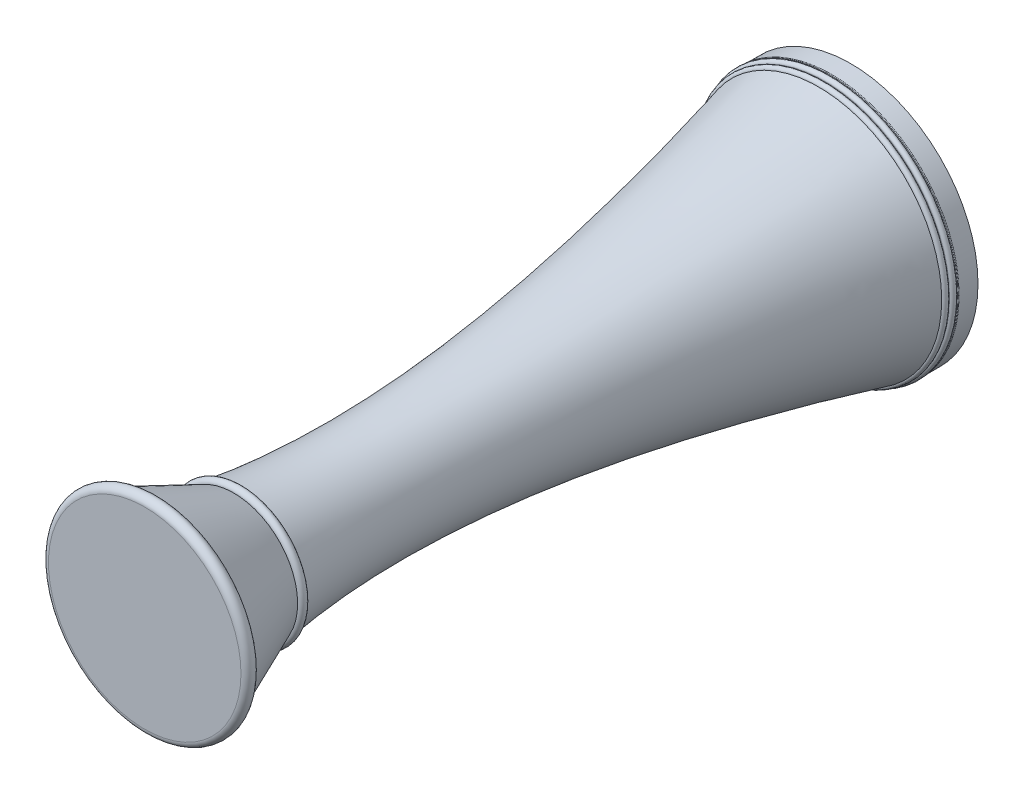
SolidWorks part; units mm, degrees
ref_plane "Front Plane" through (0, 0, 0) normal (0, 0, 1) x (1, 0, 0)
ref_plane "Top Plane" through (0, 0, 0) normal (0, 1, 0) x (1, 0, 0)
ref_plane "Right Plane" through (0, 0, 0) normal (1, 0, 0) x (0, 0, -1)
sketch "Sketch1" plane through (0, 0, 0) normal (0, 0, 1) x (1, 0, 0)
  circle A0 centre (0, 0) radius 5
  dimension "D1" = 10
extrude "Boss-Extrude1" add sketch "Sketch1" along normal blind 0.75
sketch "Sketch5" plane through (0, 0, 0) normal (0, 1, 0) x (1, 0, 0)
  line L0 (0, 0) -> (0, -50.8181) construction
sketch "Sketch7" plane through (0, 0, 0) normal (0, 1, 0) x (1, 0, 0)
  line L0 (-5, -0.75) -> (5, -0.75) construction
  line L2 (0, -0.75) -> (5, -0.75)
  line L3 (5, -0.7887) -> (0, -0.7887)
  line L4 (0, 0) -> (0, -50.8181) construction
  line L5 (0, -0.7887) -> (0, -0.75)
  arc A0 (5, -0.75) -> (5, -0.7887) centre (5, -0.7693) cw
revolve "Revolve1" add sketch "Sketch7" angle 360 about L5
sketch "Sketch8" plane through (0, 0, 0) normal (0, 1, 0) x (1, 0, 0)
  line L0 (0, -0.7887) -> (4.9111, -0.7887)
  line L1 (-5, -0.7887) -> (5, -0.7887) construction
  line L2 (4.9111, -1.0247) -> (0, -1.0247)
  line L3 (0, 0) -> (0, -50.8181) construction
  line L4 (0, -1.0247) -> (0, -0.7887)
  arc A0 (4.9111, -0.7887) -> (4.9111, -1.0247) centre (4.9111, -0.9067) cw
revolve "Revolve2" add sketch "Sketch8" angle 360 about L4
sketch "Sketch10" plane through (0, 0, 0) normal (0, 1, 0) x (1, 0, 0)
  line L0 (0, -1.0247) -> (4.8359, -1.0247)
  line L1 (-4.9111, -1.0247) -> (4.9111, -1.0247) construction
  line L2 (4.8359, -1.2631) -> (0, -1.2631)
  line L3 (0, 0) -> (0, -50.8181) construction
  line L4 (0, -1.2631) -> (0, -1.0247)
  arc A0 (4.8359, -1.0247) -> (4.8359, -1.2631) centre (4.8359, -1.1439) cw
revolve "Revolve3" add sketch "Sketch10" angle 360 about L4
sketch "Sketch11" plane through (0, 0, 0) normal (0, 1, 0) x (1, 0, 0)
  line L2 (4.8359, -1.2631) -> (1.2181, -15.5203) construction
  line L3 (1.2181, -15.5203) -> (2.5102, -23.9242) construction
  line L4 (2.5102, -23.9242) -> (0, -23.9242)
  line L5 (0, 0) -> (0, -50.8181) construction
  line L6 (0, -23.9242) -> (0, -1.2631)
  line L7 (-4.8359, -1.2631) -> (4.8359, -1.2631) construction
  line L8 (0, -1.2631) -> (4.8359, -1.2631)
  spline S0 degree 2 poles (4.8359, -1.2631) (1.2181, -15.5203) (2.5102, -23.9242) knots 0 0 0 1 1 1
revolve "Revolve4" add sketch "Sketch11" angle 360 about L6
sketch "Sketch12" plane through (0, 0, 0) normal (0, 1, 0) x (1, 0, 0)
  line L0 (0, -23.9242) -> (2.5102, -23.9242)
  line L1 (-2.5102, -23.9242) -> (2.5102, -23.9242) construction
  line L2 (2.5102, -24.2568) -> (0, -24.2568)
  line L3 (0, 0) -> (0, -50.8181) construction
  line L4 (0, -24.2568) -> (0, -23.9242)
  arc A0 (2.5102, -23.9242) -> (2.5102, -24.2568) centre (2.5102, -24.0905) cw
revolve "Revolve5" add sketch "Sketch12" angle 360 about L4
sketch "Sketch14" plane through (0, 0, 24.2568) normal (0, 0, 1) x (1, 0, 0)
  circle A0 centre (0, 0) radius 2.5102
extrude "Boss-Extrude2" add sketch "Sketch14" along normal blind 3 draft 23 draft outward yes
sketch "Sketch15" plane through (0, 0, 0) normal (0, 1, 0) x (1, 0, 0)
  line L0 (0, -27.2568) -> (3.7837, -27.2568)
  line L1 (-3.7837, -27.2568) -> (3.7837, -27.2568) construction
  line L2 (3.7837, -27.7575) -> (0, -27.7575)
  line L3 (0, 0) -> (0, -50.8181) construction
  line L4 (0, -27.7575) -> (0, -27.2568)
  arc A0 (3.7837, -27.2568) -> (3.7837, -27.7575) centre (3.7837, -27.5072) cw
revolve "Revolve6" add sketch "Sketch15" angle 360 about L4
sketch "Sketch24" plane through (0, 0, 27.7575) normal (0, 0, 1) x (1, 0, 0)
  point P0 (0, 0)
sketch "Sketch27" plane through (0, 0, 0) normal (0, 1, 0) x (1, 0, 0)
  line L1 (0, -23.2057) -> (0, -41.8863) construction
